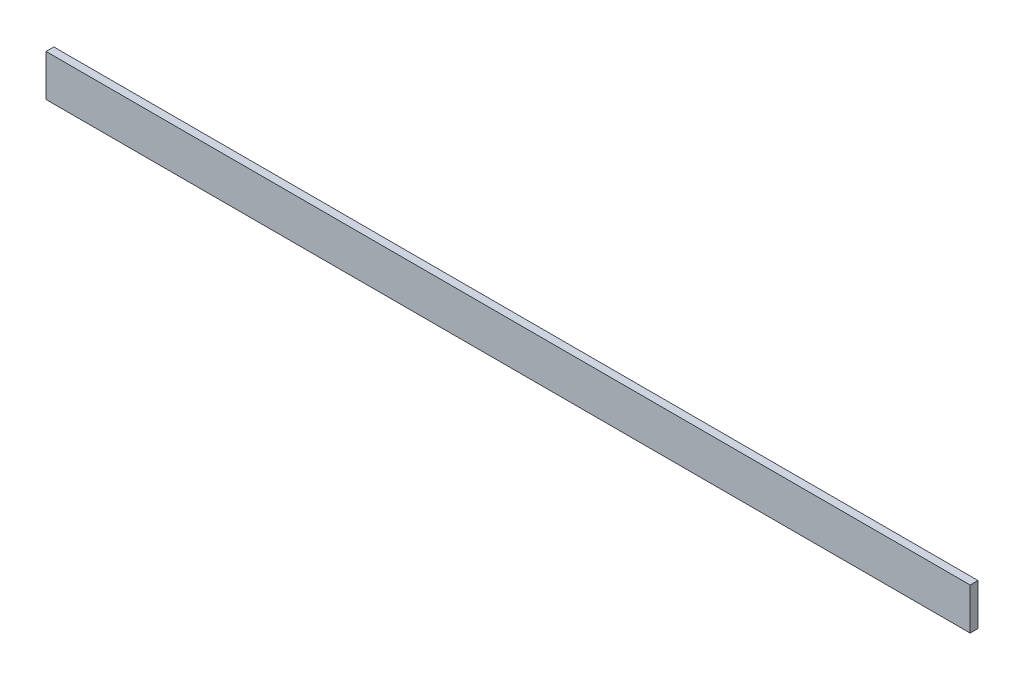
SolidWorks part; units mm, degrees
ref_plane "Alzado" through (0, 0, 0) normal (0, 0, 1) x (1, 0, 0)
ref_plane "Planta" through (0, 0, 0) normal (0, 1, 0) x (1, 0, 0)
ref_plane "Vista lateral" through (0, 0, 0) normal (1, 0, 0) x (0, 0, -1)
sketch "Croquis1" plane through (0, 0, 0) normal (0, 0, 1) x (1, 0, 0)
  line L1 (0, 0) -> (1127.6, 0)
  line L2 (0, 0) -> (0, 50.8)
  line L3 (0, 50.8) -> (1127.6, 50.8)
  line L4 (1127.6, 0) -> (1127.6, 50.8)
  dimension "D1" = 50.8
  dimension "D2" = 1127.6
extrude "Saliente-Extruir1" add sketch "Croquis1" along normal blind 9.525
